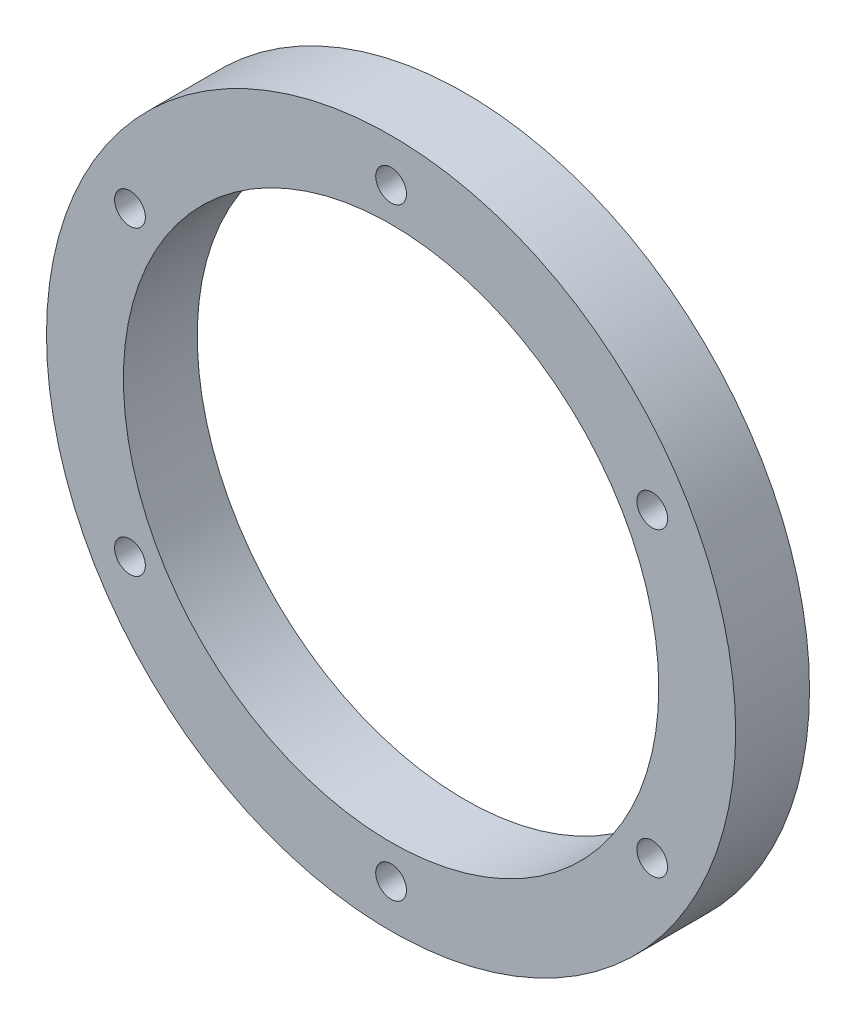
SolidWorks part; units mm, degrees
material "ABS"
ref_plane "前视基准面" through (0, 0, 0) normal (0, 0, 1) x (1, 0, 0)
ref_plane "上视基准面" through (0, 0, 0) normal (0, 1, 0) x (1, 0, 0)
ref_plane "右视基准面" through (0, 0, 0) normal (1, 0, 0) x (0, 0, -1)
sketch "草图1" plane through (0, 0, 0) normal (0, 0, 1) x (1, 0, 0)
  circle A0 centre (0, 0) radius 28
  circle A1 centre (0, 0) radius 24.5 construction
  circle A2 centre (0, 24.5) radius 1.25
  circle A3 centre (0, 0) radius 21.75
  circle A4 centre (21.2176, 12.25) radius 1.25
  circle A5 centre (21.2176, -12.25) radius 1.25
  circle A6 centre (0, -24.5) radius 1.25
  circle A7 centre (-21.2176, -12.25) radius 1.25
  circle A8 centre (-21.2176, 12.25) radius 1.25
  point P7 (26.3676, -15.567)
  point P8 (0, 0)
  point P19 (0, 0)
  dimension "D1" = 56
  dimension "D2" = 49
  dimension "D3" = 2.5
  dimension "D4" = 43.5
  dimension "D5" = 6
extrude "凸台-拉伸1" add sketch "草图1" along normal blind 6
